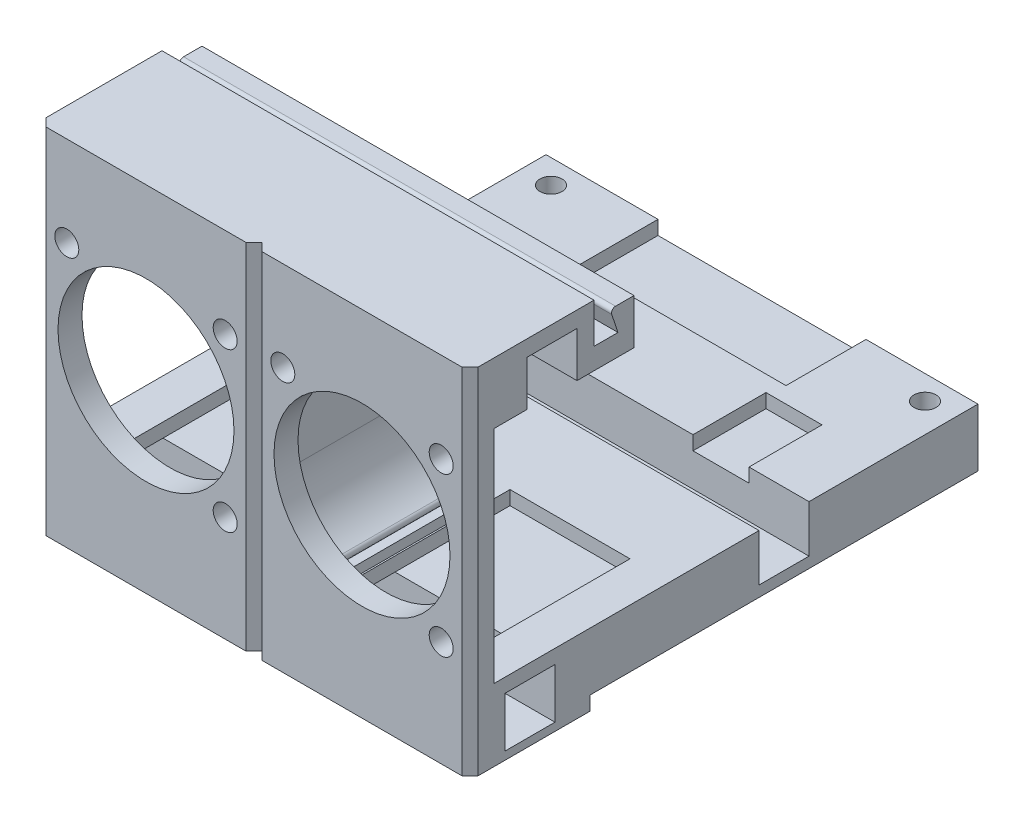
SolidWorks part; units mm, degrees
ref_plane "Front Plane" through (0, 0, 0) normal (0, 0, 1) x (1, 0, 0)
ref_plane "Top Plane" through (0, 0, 0) normal (0, 1, 0) x (1, 0, 0)
ref_plane "Right Plane" through (0, 0, 0) normal (1, 0, 0) x (0, 0, -1)
sketch "Sketch1" plane through (0, 0, 0) normal (0, 1, 0) x (1, 0, 0)
  line L0 (-23.375, 28.75) -> (23.375, 28.75) construction
  line L1 (-27, 31.75) -> (27, 31.75)
  line L2 (-27, 31.75) -> (-27, -31.75)
  line L3 (-27, -31.75) -> (27, -31.75)
  line L4 (27, 31.75) -> (27, -31.75)
  line L5 (-27, 31.75) -> (27, -31.75) construction
  line L6 (-27, -31.75) -> (27, 31.75) construction
  line L11 (0, 0) -> (0, 28.75) construction
  circle A0 centre (-23.375, 28.75) radius 1.375
  circle A1 centre (23.375, 28.75) radius 1.375
  circle A2 centre (0, -5.5) radius 1.375
  point P0 (0, 0)
  dimension "D3" = 2.75
  dimension "D1" = 54
  dimension "D2" = 63.5
  dimension "D4" = 3
  dimension "D5" = 46.75
  dimension "D6" = 34.25
extrude "Boss-Extrude1" add sketch "Sketch1" along normal blind 9
sketch "Sketch2" plane through (0, 9, 0) normal (0, 1, 0) x (1, 0, 0)
  line L0 (27, -31.75) -> (27, 31.75) construction
  line L1 (-27, -31.75) -> (27, -31.75)
  line L2 (-27, -31.75) -> (-27, -28.75)
  line L3 (-27, -28.75) -> (27, -28.75)
  line L4 (27, -31.75) -> (27, -28.75)
  dimension "D1" = 3
extrude "Boss-Extrude2" add sketch "Sketch2" along normal offset from surface (35.25 mm away) 44.25 up to face at (0, 0, 0)
sketch "Sketch3" plane through (0, 0, 31.75) normal (0, 0, 1) x (1, 0, 0)
  line L0 (-27, 9) -> (27, 9) construction
  line L1 (-27, 44.25) -> (-27, 0) construction
  line L2 (27, 44.25) -> (27, 0) construction
  line L3 (0, 10.6) -> (0, 23.1) construction
  line L4 (-27, 10.6) -> (27, 10.6) construction
  line L5 (-23.4, 33) -> (-3.6, 33) construction
  line L6 (-23.4, 33) -> (-23.4, 13.2) construction
  line L7 (-23.4, 13.2) -> (-3.6, 13.2) construction
  line L8 (-3.6, 33) -> (-3.6, 13.2) construction
  line L9 (-23.4, 33) -> (-3.6, 13.2) construction
  line L10 (-23.4, 13.2) -> (-3.6, 33) construction
  line L11 (3.6, 33) -> (23.4, 33) construction
  line L12 (3.6, 33) -> (3.6, 13.2) construction
  line L13 (3.6, 13.2) -> (23.4, 13.2) construction
  line L14 (23.4, 33) -> (23.4, 13.2) construction
  line L15 (3.6, 33) -> (23.4, 13.2) construction
  line L16 (3.6, 13.2) -> (23.4, 33) construction
  line L17 (-2.5, 23.1) -> (-3.6, 23.1) construction
  line L18 (2.5, 23.1) -> (3.6, 23.1) construction
  line L21 (27, 9) -> (-27, 9) construction
  line L22 (-2.5, 23.1) -> (2.5, 23.1) construction
  circle A0 centre (-13.5, 23.1) radius 11
  circle A1 centre (13.5, 23.1) radius 11
  circle A2 centre (-23.4, 33) radius 1.5
  circle A3 centre (-3.6, 13.2) radius 1.5
  circle A4 centre (3.6, 33) radius 1.5
  circle A5 centre (23.4, 13.2) radius 1.5
  circle A6 centre (-3.6, 33) radius 1.5
  circle A7 centre (23.4, 33) radius 1.5
  point P6 (-13.5, 23.1)
  point P13 (13.5, 23.1)
  dimension "D1" = 3
  dimension "D2" = 22
  dimension "D9" = 3
  dimension "D3" = 19.8
  dimension "D4" = 19.8
  dimension "D5" = 12.5
  dimension "D6" = 1.6
  dimension "D7" = 13.5
  dimension "D8" = 13.5
extrude "Cut-Extrude1" cut sketch "Sketch3" against normal through all
sketch "Sketch4" plane through (0, 0, 0) normal (0, -1, 0) x (-1, 0, 0)
  line L0 (-27, -31.75) -> (-27, 31.75) construction
  line L1 (27, 31.75) -> (-27, 31.75)
  line L2 (27, 31.75) -> (27, -16.75)
  line L3 (27, -16.75) -> (-27, -16.75)
  line L4 (-27, 31.75) -> (-27, -16.75)
  line L5 (27, -31.75) -> (-27, -31.75) construction
  dimension "D1" = 15
extrude "Cut-Extrude2" cut sketch "Sketch4" against normal blind 1.75
sketch "Sketch5" plane through (0, 0, 28.75) normal (0, 0, -1) x (-1, 0, 0)
  line L0 (-13.5, 23.1) -> (13.5, 23.1) construction
  line L1 (0, 9) -> (0, 23.1) construction
  line L2 (-1.25, 23.1) -> (-1.25, 29.8413)
  line L3 (-27, 9) -> (27, 9) construction
  line L15 (-13.5, 23.1) -> (-13.5, 34.1) construction
  line L16 (13.5, 23.1) -> (13.5, 34.1) construction
  line L18 (-1.25, 23.1) -> (-1.25, 19.35)
  line L19 (-5.8167, 10.6) -> (0, 10.6)
  line L20 (1.5, 23.1) -> (1.5, 16.8865)
  line L21 (0, 10.6) -> (0.6, 10.6)
  line L22 (0.6, 10.6) -> (0.6, 13.2)
  line L23 (0.6, 13.2) -> (3.6, 13.2) construction
  line L24 (-1.25, 23.1) -> (0, 23.1) construction
  line L25 (1.5, 23.1) -> (1.5, 25.3221)
  line L26 (9.4, 36.6) -> (-0.6, 36.6)
  line L27 (-0.6, 36.6) -> (-0.6, 33)
  line L28 (-3.6, 33) -> (-0.6, 33) construction
  line L29 (0, 23.1) -> (1.5, 23.1) construction
  arc A13 (-0.8437, 31.8155) -> (-0.6, 33) centre (-3.6, 33) ccw
  circle A16 centre (13.5, 23.1) radius 11 construction
  circle A17 centre (-13.5, 23.1) radius 11 construction
  arc A18 (6.5989, 13.283) -> (23.317, 30.0011) centre (13.5, 23.1) ccw construction
  arc A19 (23.317, 30.0011) -> (20.4011, 32.917) centre (23.4, 33) ccw construction
  arc A20 (3.683, 16.1989) -> (1.5, 15.3424) centre (3.6, 13.2) ccw construction
  arc A21 (3.683, 16.1989) -> (6.5989, 13.283) centre (13.5, 23.1) ccw construction
  arc A22 (6.5989, 13.283) -> (3.683, 16.1989) centre (3.6, 13.2) ccw construction
  arc A24 (23.317, 30.0011) -> (20.4011, 32.917) centre (13.5, 23.1) ccw construction
  arc A25 (20.4011, 32.917) -> (23.317, 30.0011) centre (23.4, 33) ccw construction
  arc A26 (-6.0428, 11.5459) -> (-1.25, 19.35) centre (-10, 19.35) ccw
  arc A27 (1.5, 23.1) -> (3.683, 16.1989) centre (13.5, 23.1) ccw construction
  arc A28 (20.4011, 32.917) -> (1.5, 23.1) centre (13.5, 23.1) ccw construction
  arc A29 (0.6, 13.2) -> (6.5989, 13.283) centre (3.6, 13.2) ccw construction
  arc A30 (0.9375, 14.5824) -> (0.6, 13.2) centre (3.6, 13.2) ccw
  arc A31 (1.5, 16.8865) -> (0.9375, 14.5824) centre (-3.5, 16.8865) cw
  arc A32 (-5.8167, 10.6) -> (-6.0428, 11.5459) centre (-5.8167, 11.1) cw
  arc A33 (-0.6, 33) -> (-1.25, 31.1352) centre (-3.6, 33) ccw construction
  arc A34 (-1.25, 29.8413) -> (-0.8437, 31.8155) centre (3.75, 29.8413) cw
  arc A37 (9.4, 36.6) -> (5.6012, 34.3559) centre (13.5, 25.3221) ccw
  circle A38 centre (3.6, 33) radius 1.5 construction
  arc A39 (4.4058, 34.2652) -> (2.5751, 31.9047) centre (3.6, 33) ccw
  arc A40 (2.7848, 30.7244) -> (1.5, 25.3221) centre (13.5, 25.3221) ccw
  arc A41 (5.6012, 34.3559) -> (4.4058, 34.2652) centre (4.9429, 35.1087) cw
  arc A42 (2.7848, 30.7244) -> (2.5751, 31.9047) centre (1.8918, 31.1746) ccw
  point P28 (3.75, 46.2217)
  point P29 (-8, 32.5868)
  point P30 (2.5213, 27.9443)
  point P40 (-10, 10.6)
  point P62 (9.4, 36.6)
  dimension "D2" = 3
  dimension "D4" = 1.6
  dimension "D1" = 3
  dimension "D3" = 12
  dimension "D6" = 10
  dimension "D7" = 5
  dimension "D8" = 0.5
  dimension "D9" = 5
  dimension "D12" = 1
  dimension "D5" = 12.25
  dimension "D10" = 10
  dimension "D11" = 13.5
extrude "Boss-Extrude3" add sketch "Sketch5" along normal blind 17.5
sketch "Sketch6" plane through (0, 0, 28.75) normal (0, 0, -1) x (-1, 0, 0)
  line L0 (27, 44.25) -> (27, 9) construction
  line L1 (-27, 44.25) -> (27, 44.25)
  line L2 (-27, 44.25) -> (-27, 36.6)
  line L3 (-27, 36.6) -> (27, 36.6)
  line L4 (27, 44.25) -> (27, 36.6)
  point P7 (-0.6, 36.6)
extrude "Boss-Extrude5" add sketch "Sketch6" along normal up to surface (17.5 mm away) up to face at (-0.7624, 24.7849, 11.25)
fillet "Fillet2" radius 3 2 edges at (-9.4, 36.6, 20) (0.6, 36.6, 20)
sketch "Sketch8" plane through (0, 9, 0) normal (0, 1, 0) x (1, 0, 0)
  line L0 (27, -28.75) -> (-27, -28.75) construction
  line L1 (22, -28.75) -> (7, -28.75)
  line L2 (22, -28.75) -> (22, -6.75)
  line L3 (22, -6.75) -> (7, -6.75)
  line L4 (-22, -28.75) -> (-22, -6.75)
  line L5 (27, -28.75) -> (27, 31.75) construction
  line L6 (0, 0) -> (0, -6.75) construction
  line L7 (-7, -6.75) -> (-22, -6.75)
  line L8 (27, 31.75) -> (-27, 31.75) construction
  line L9 (-13, 31.75) -> (13, 31.75)
  line L10 (-13, 31.75) -> (-13, 21.75)
  line L11 (-13, 21.75) -> (0, 21.75)
  line L12 (13, 31.75) -> (13, 21.75)
  line L13 (0, 0) -> (0, 21.75) construction
  line L14 (7, -6.75) -> (7, -28.75)
  line L16 (-7, -6.75) -> (-7, -28.75)
  line L17 (-27, 31.75) -> (-27, -28.75) construction
  line L18 (-7, -28.75) -> (-22, -28.75)
  line L23 (0, 21.75) -> (13, 21.75)
  line L25 (12.5, 19.75) -> (19.5, 19.75)
  line L26 (12.5, 19.75) -> (12.5, 9.75)
  line L27 (12.5, 9.75) -> (19.5, 9.75)
  line L28 (19.5, 19.75) -> (19.5, 9.75)
  line L29 (12.5, 19.75) -> (19.5, 9.75) construction
  line L30 (12.5, 9.75) -> (19.5, 19.75) construction
  point P13 (16, 14.75)
  dimension "D3" = 7
  dimension "D1" = 5
  dimension "D2" = 22
  dimension "D4" = 26
  dimension "D5" = 10
  dimension "D6" = 7
  dimension "D7" = 5
  dimension "D8" = 12
  dimension "D9" = 10
  dimension "D10" = 7
  dimension "D11" = 7.5
extrude "Cut-Extrude4" cut sketch "Sketch8" against normal blind 1.75
sketch "Sketch7" plane through (27, 0, 0) normal (1, 0, 0) x (0, 0, -1)
  line L0 (-31.75, 0) -> (-16.75, 0) construction
  line L1 (7.5, 1.75) -> (7.5, 9) construction
  line L2 (-28.75, 9) -> (31.75, 9) construction
  line L3 (-24.25, 9) -> (-24.25, 36.6) construction
  line L4 (-11.25, 36.6) -> (-28.75, 36.6) construction
  line L5 (-24.25, 36.6) -> (-24.25, 44.25) construction
  line L6 (-31.75, 44.25) -> (-11.25, 44.25) construction
  line L7 (31.75, 1.75) -> (-16.75, 1.75) construction
  line L14 (-24.25, 9) -> (-24.25, 0) construction
  line L15 (-27.375, 7.25) -> (-21.125, 7.25)
  line L16 (-27.375, 7.25) -> (-27.375, 1)
  line L17 (-27.375, 1) -> (-21.125, 1)
  line L18 (-21.125, 7.25) -> (-21.125, 1)
  line L19 (-27.375, 7.25) -> (-21.125, 1) construction
  line L20 (-27.375, 1) -> (-21.125, 7.25) construction
  line L21 (-24.625, 36) -> (-18.375, 36)
  line L22 (-24.625, 36) -> (-24.625, 42.25)
  line L23 (-24.625, 42.25) -> (-18.375, 42.25)
  line L24 (-18.375, 36) -> (-18.375, 42.25)
  line L25 (-24.625, 36) -> (-18.375, 42.25) construction
  line L26 (-24.625, 42.25) -> (-18.375, 36) construction
  line L27 (-21.5, 44.25) -> (-21.5, 39.125) construction
  line L28 (-6.75, 7.25) -> (-28.75, 7.25) construction
  line L29 (4.375, 3.1) -> (10.625, 3.1)
  line L30 (4.375, 3.1) -> (4.375, 9)
  line L31 (4.375, 9) -> (10.625, 9)
  line L32 (10.625, 3.1) -> (10.625, 9)
  line L33 (4.375, 3.1) -> (10.625, 9) construction
  line L34 (4.375, 9) -> (10.625, 3.1) construction
  point P0 (-21.5, 39.125)
  point P18 (-24.25, 4.125)
  point P20 (7.5, 6.05)
  dimension "D1" = 5.9
  dimension "D2" = 2
  dimension "D3" = 6.25
extrude "Cut-Extrude3" cut sketch "Sketch7" against normal through all
chamfer "Chamfer2" distance 1 angle 45 2 edges at (-27, 22.125, 31.75) (27, 22.125, 31.75)
sketch "Sketch9" plane through (0, 44.25, 0) normal (0, 1, 0) x (1, 0, 0)
  line L0 (0, -31.75) -> (0, -30.75) construction
  line L1 (-26, -31.75) -> (26, -31.75) construction
  line L2 (-1, -31.75) -> (0, -30.75)
  line L3 (0, -30.75) -> (1, -31.75)
  line L4 (1, -31.75) -> (-1, -31.75)
  line L5 (-27, -30.75) -> (-26, -31.75) construction
extrude "Cut-Extrude5" cut sketch "Sketch9" against normal through all
sketch "Sketch10" plane through (27, 0, 0) normal (1, 0, 0) x (0, 0, -1)
  line L0 (-11.25, 44.25) -> (-16.25, 44.25)
  line L1 (-30.75, 44.25) -> (-11.25, 44.25) construction
  line L2 (-16.25, 44.25) -> (-16.25, 39.25)
  line L3 (-16.25, 39.25) -> (-13.25, 39.25)
  line L4 (-13.25, 39.25) -> (-14.0306, 41.5919)
  line L5 (-13.5563, 42.25) -> (-11.25, 42.25)
  line L6 (-11.25, 44.25) -> (-11.25, 36.6) construction
  line L7 (-11.25, 42.25) -> (-11.25, 44.25)
  arc A0 (-14.0306, 41.5919) -> (-13.5563, 42.25) centre (-13.5563, 41.75) cw
  point P13 (-14.25, 42.25)
  dimension "D6" = 0.5
  dimension "D1" = 5
  dimension "D2" = 2
  dimension "D3" = 2
  dimension "D4" = 5
  dimension "D5" = 2
extrude "Cut-Extrude6" cut sketch "Sketch10" against normal through all
sketch "Sketch13" plane through (0, 9, 0) normal (0, 1, 0) x (1, 0, 0)
  line L0 (7, -6.75) -> (7, -28.75) construction
  line L1 (7, -28.3698) -> (-1.6809, -28.3698)
  line L2 (7, -28.3698) -> (7, -10.1957)
  line L3 (7, -10.1957) -> (-1.6809, -10.1957)
  line L4 (-1.6809, -28.3698) -> (-1.6809, -10.1957)
extrude "Boss-Extrude6" add sketch "Sketch13" along normal offset from surface (1.2 mm away) 0.2 from offset 0.2 separate body up to face at (2.6083, 10.6, 20)
